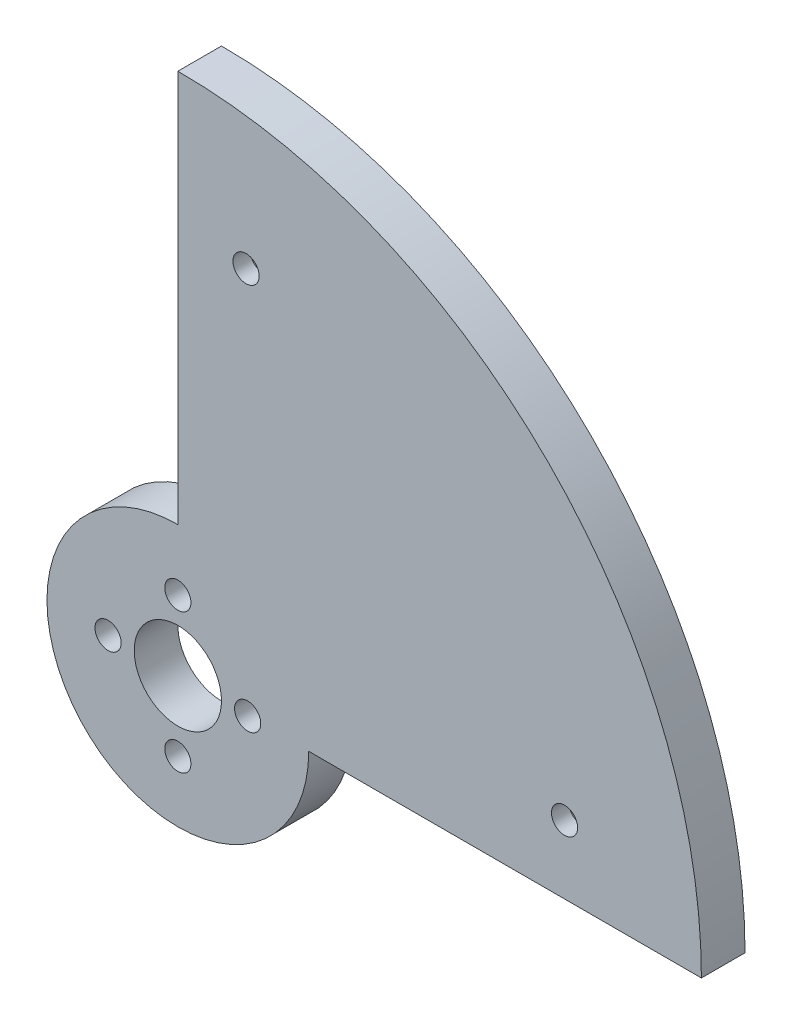
SolidWorks part; units mm, degrees
ref_plane "Front Plane" through (0, 0, 0) normal (0, 0, 1) x (1, 0, 0)
ref_plane "Top Plane" through (0, 0, 0) normal (0, 1, 0) x (1, 0, 0)
ref_plane "Right Plane" through (0, 0, 0) normal (1, 0, 0) x (0, 0, -1)
sketch "Sketch1" plane through (0, 0, 0) normal (0, 0, 1) x (1, 0, 0)
  line L0 (0, 0) -> (0, 60)
  line L1 (60, 0) -> (0, 0)
  line L2 (0, 0) -> (51.9615, -30) construction
  circle A0 centre (0, 0) radius 60 construction
  arc A1 (0, 60) -> (60, 0) centre (0, 0) cw
  dimension "D1" = 120
  dimension "D2" = 90
  dimension "D3" = 120
extrude "Boss-Extrude1" add sketch "Sketch1" along normal blind 5
sketch "Sketch2" plane through (0, 0, 5) normal (0, 0, 1) x (1, 0, 0)
  circle A0 centre (0, 0) radius 15
  dimension "D1" = 30
extrude "Boss-Extrude2" add sketch "Sketch2" against normal blind 5
sketch "Sketch3" plane through (0, 0, 5) normal (0, 0, 1) x (1, 0, 0)
  circle A0 centre (0, 0) radius 5
  dimension "D1" = 10
extrude "Cut-Extrude1" cut sketch "Sketch3" against normal blind 5
sketch "Sketch4" plane through (0, 0, 5) normal (0, 0, 1) x (1, 0, 0)
  line L0 (0, 60) -> (0, 15) construction
  line L1 (15, 0) -> (60, 0) construction
  line L2 (7.8142, 44.3163) -> (0, 0) construction
  line L3 (0, 0) -> (44.3163, 7.8142) construction
  arc A0 (0, 45) -> (45, 0) centre (0, 0) cw construction
  arc A1 (60, 0) -> (0, 60) centre (0, 0) ccw construction
  circle A2 centre (7.8142, 44.3163) radius 1.5
  circle A3 centre (44.3163, 7.8142) radius 1.5
  dimension "D1" = 45
  dimension "D2" = 3
  dimension "D3" = 3
  dimension "D4" = 10
  dimension "D5" = 10
extrude "Cut-Extrude2" cut sketch "Sketch4" against normal blind 2
sketch "Sketch5" plane through (0, 0, 0) normal (0, 0, 1) x (1, 0, 0)
  line L2 (8.7722, 35.7899) -> (-0.1103, 25.2997)
  line L3 (-0.0358, 41.9822) -> (-0.1103, 25.2997)
  arc A0 (-0.0358, 41.9822) -> (8.7722, 35.7899) centre (-30, -10) cw
  dimension "D3" = 60
extrude "Cut-Extrude3" cut sketch "Sketch5" along normal blind 2 contours L2 L3 A0
sketch "Sketch6" plane through (0, 0, 5) normal (0, 0, 1) x (1, 0, 0)
  line L0 (0, 0) -> (0, 60) construction
  circle A0 centre (0, 8) radius 1.5
  circle A1 centre (8, 0) radius 1.5
  circle A2 centre (0, -8) radius 1.5
  circle A3 centre (-8, 0) radius 1.5
  point P12 (0, 0)
  dimension "D1" = 8
  dimension "D2" = 3
  dimension "D3" = 4
extrude "Cut-Extrude4" cut sketch "Sketch6" against normal blind 10
